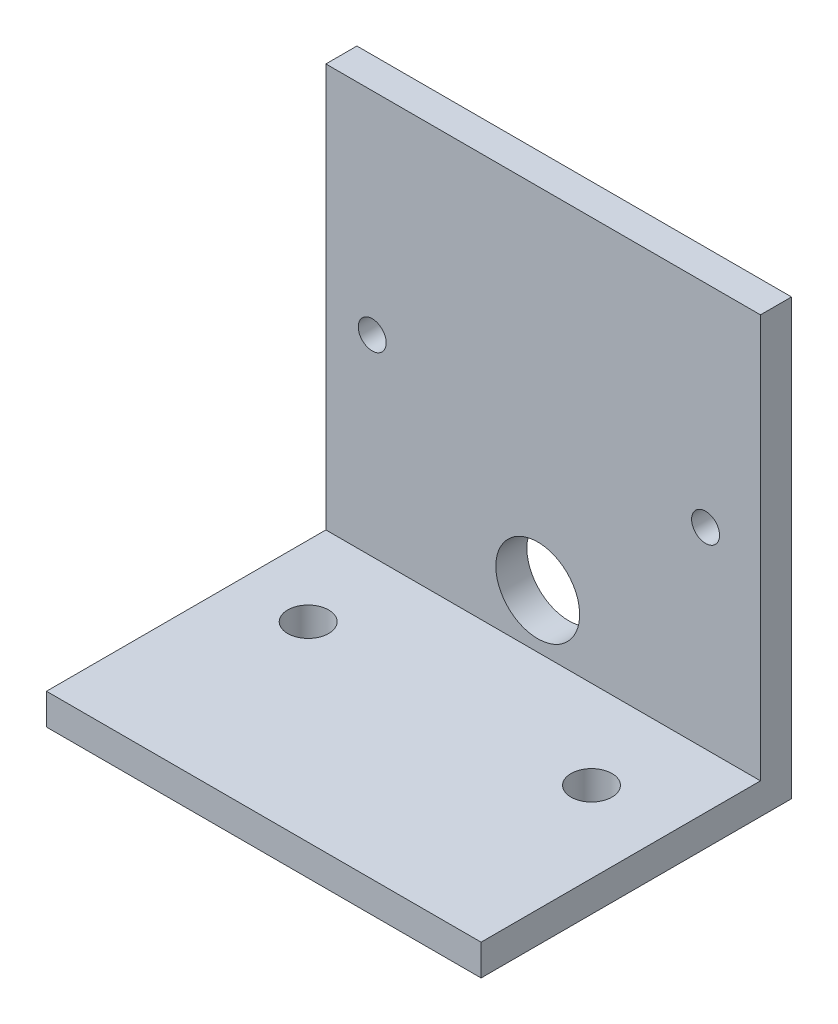
SolidWorks part; units mm, degrees
ref_plane "Plan de face" through (0, 0, 0) normal (0, 0, 1) x (1, 0, 0)
ref_plane "Plan de dessus" through (0, 0, 0) normal (0, 1, 0) x (1, 0, 0)
ref_plane "Plan de droite" through (0, 0, 0) normal (1, 0, 0) x (0, 0, -1)
sketch "Esquisse1" plane through (0, 0, 0) normal (0, 0, 1) x (1, 0, 0)
  line L1 (-35, -35) -> (35, -35)
  line L2 (-35, -35) -> (-35, 35)
  line L3 (-35, 35) -> (35, 35)
  line L4 (35, -35) -> (35, 35)
  line L5 (-35, -35) -> (35, 35) construction
  line L6 (-35, 35) -> (35, -35) construction
  point P0 (0, 0)
  dimension "D1" = 70
  dimension "D2" = 70
extrude "Boss.-Extru.1" add sketch "Esquisse1" along normal blind 50
sketch "Esquisse2" plane through (35, 0, 0) normal (1, 0, 0) x (0, 0, -1)
  line L8 (-5, -30) -> (-5, 30)
  line L9 (-5, 30) -> (-45, 30)
  line L10 (-45, 30) -> (-45, -30)
  line L11 (-45, -30) -> (-5, -30)
  line L12 (-5, -30) -> (-5, 56.8641)
  line L13 (-5, 56.8641) -> (-128.1376, 56.8641)
  line L14 (-128.1376, 56.8641) -> (-128.1376, -30)
  line L15 (-128.1376, -30) -> (-5, -30)
  dimension "D1" = 5
extrude "Enlèv. mat.-Extru.1" cut sketch "Esquisse2" against normal blind 217
hole_wizard "Dégagement M41" positions "Esquisse4" profile "Esquisse3" hole size "M4" standard "JIS" end condition through all
sketch "Esquisse4" plane through (0, 0, 0) normal (0, 0, -1) x (-1, 0, 0)
  point P0 (-26.1576, 0.9464)
  point P2 (27.5331, 0.9464)
sketch "Esquisse3" plane through (26.1576, 0.9464, 0) normal (1, 0, 0) x (0, 1, 0)
  line L0 (0, 0) -> (0, 50)
  line L1 (0, 50) -> (2.25, 50)
  line L2 (2.25, 50) -> (2.25, 0)
  line L5 (2.25, 0) -> (0, 0)
  line L11 (0, -6.35) -> (0, 107.95) construction
  dimension "Diamètre du perçage jusqu'au prochain" = 4.5
  dimension "Profondeur du perçage jusqu'au prochain" = 50
hole_wizard "Dégagement M121" positions "Esquisse6" profile "Esquisse5" hole size "M12" standard "JIS" end condition through all
sketch "Esquisse6" plane through (0, 0, 0) normal (0, 0, -1) x (-1, 0, 0)
  point P0 (0.8755, -21.3664)
sketch "Esquisse5" plane through (-0.8755, -21.3664, 0) normal (1, 0, 0) x (0, 1, 0)
  line L0 (0, 0) -> (0, 50)
  line L1 (0, 50) -> (6.75, 50)
  line L2 (6.75, 50) -> (6.75, 0)
  line L5 (6.75, 0) -> (0, 0)
  line L11 (0, -6.35) -> (0, 107.95) construction
  dimension "Diamètre du perçage jusqu'au prochain" = 13.5
  dimension "Profondeur du perçage jusqu'au prochain" = 50
hole_wizard "Dégagement M61" positions "Esquisse9" profile "Esquisse7" hole size "M6" standard "JIS" end condition through all
sketch "Esquisse9" plane through (0, -30, 0) normal (0, 1, 0) x (1, 0, 0)
  point P0 (-23.6203, -19.2318)
  point P2 (22.0152, -19.2318)
sketch "Esquisse7" plane through (-23.6203, -30, 19.2318) normal (1, 0, 0) x (0, 0, 1)
  line L0 (0, 0) -> (0, 5)
  line L1 (0, 5) -> (3.3, 5)
  line L2 (3.3, 5) -> (3.3, 0)
  line L5 (3.3, 0) -> (0, 0)
  line L11 (0, -6.35) -> (0, 107.95) construction
  dimension "Diamètre du perçage jusqu'au prochain" = 6.6
  dimension "Profondeur du perçage jusqu'au prochain" = 5
